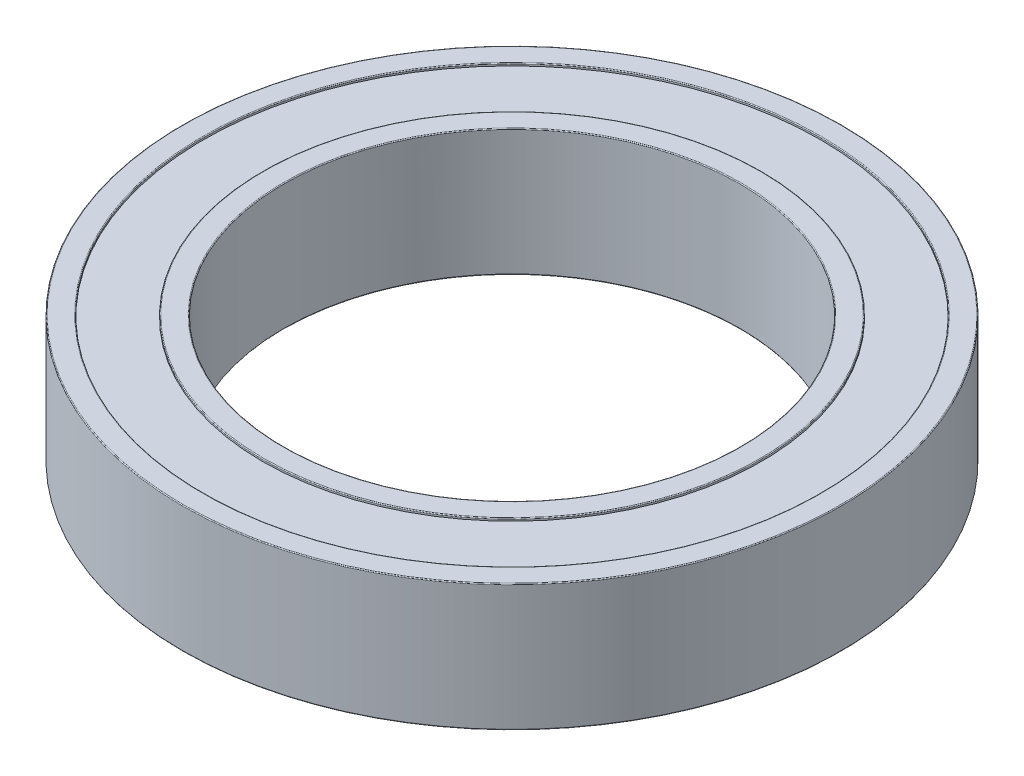
SolidWorks part; units mm, degrees
ref_plane "Front Plane" through (0, 0, 0) normal (0, 0, 1) x (1, 0, 0)
ref_plane "Top Plane" through (0, 0, 0) normal (0, 1, 0) x (1, 0, 0)
ref_plane "Right Plane" through (0, 0, 0) normal (1, 0, 0) x (0, 0, -1)
sketch "Sketch1" plane through (0, 0, 0) normal (0, 0, 1) x (1, 0, 0)
  line L0 (0, 0) -> (0, 11.7584) construction
  line L1 (0, 0) -> (-16.5, 0) construction
  line L2 (-16.5, 0) -> (-16.5, 7.1092) construction
  line L3 (-19.5, 3.75) -> (-18.25, 3.75)
  line L4 (-18.25, 3.75) -> (-18.25, 2.5)
  line L5 (-19.5, 3.75) -> (-19.5, -3.75)
  line L6 (-19.5, -3.75) -> (-18.25, -3.75)
  line L7 (-18.25, -3.75) -> (-18.25, -2.5)
  line L8 (-14.75, -3.75) -> (-14.75, -2.5)
  line L9 (-13.5, -3.75) -> (-14.75, -3.75)
  line L10 (-13.5, 3.75) -> (-13.5, -3.75)
  line L11 (-13.5, 3.75) -> (-14.75, 3.75)
  line L12 (-14.75, 3.75) -> (-14.75, 2.5)
  circle A0 centre (-16.5, 0) radius 2.5 construction
  arc A1 (-18.25, -2.5) -> (-18.25, 2.5) centre (-15.1275, 0) cw
  arc A2 (-14.75, -2.5) -> (-14.75, 2.5) centre (-17.8725, 0) ccw
  point P21 (-19.5, 0)
  dimension "D1" = 5
  dimension "D5" = 7.5
  dimension "D6" = 4
  dimension "D2" = 13.5
  dimension "D3" = 3
  dimension "D4" = 1.25
  dimension "D7" = 1.25
revolve "Revolve1" add sketch "Sketch1" angle 360 about L0
sketch "Sketch2" plane through (0, 0, 0) normal (0, 0, 1) x (1, 0, 0)
  line L0 (-16.5, 2.5) -> (-16.5, -2.5)
  circle A0 centre (-16.5, 0) radius 2.5 construction
  arc A1 (-16.5, 2.5) -> (-16.5, -2.5) centre (-16.5, 0) ccw
revolve "Revolve2" add sketch "Sketch2" angle 360 about L0
pattern_circular "CirPattern1" count 30 over 360 about axis through (0, 0, 0) along (0, 1, 0) of "Revolve2"
sketch "Sketch3" plane through (0, 0, 0) normal (0, 0, 1) x (1, 0, 0)
  line L0 (-18.25, 3.35) -> (-18.25, 3.6)
  line L1 (-18.25, 3.75) -> (-18.25, 2.5) construction
  line L2 (-18.25, 3.6) -> (-13.5, 3.6)
  line L3 (-13.5, 3.75) -> (-13.5, -3.75) construction
  line L4 (-13.5, 3.6) -> (-13.5, 3.35)
  line L5 (-13.5, 3.35) -> (-18.25, 3.35)
  line L6 (-19.5, 3.75) -> (-18.25, 3.75) construction
  line L7 (-16.5, 0) -> (-18.25, 0) construction
  line L8 (-13.5, -3.6) -> (-13.5, -3.35)
  line L9 (-13.5, -3.35) -> (-18.25, -3.35)
  line L10 (-18.25, -3.35) -> (-18.25, -3.6)
  line L11 (-18.25, -3.6) -> (-13.5, -3.6)
  dimension "D1" = 0.15
  dimension "D2" = 0.25
revolve "Revolve3" add sketch "Sketch3" angle 360 about L0
fillet "Fillet1" radius 0.05 4 edges at (0, -3.75, -19.5) (0, -3.75, -18.25) (0, 3.75, -18.25) (0, 3.75, -19.5)
fillet "Fillet2" radius 0.05 4 edges at (0, -3.75, -14.75) (0, -3.75, -13.5) (0, 3.75, -13.5) (0, 3.75, -14.75)
